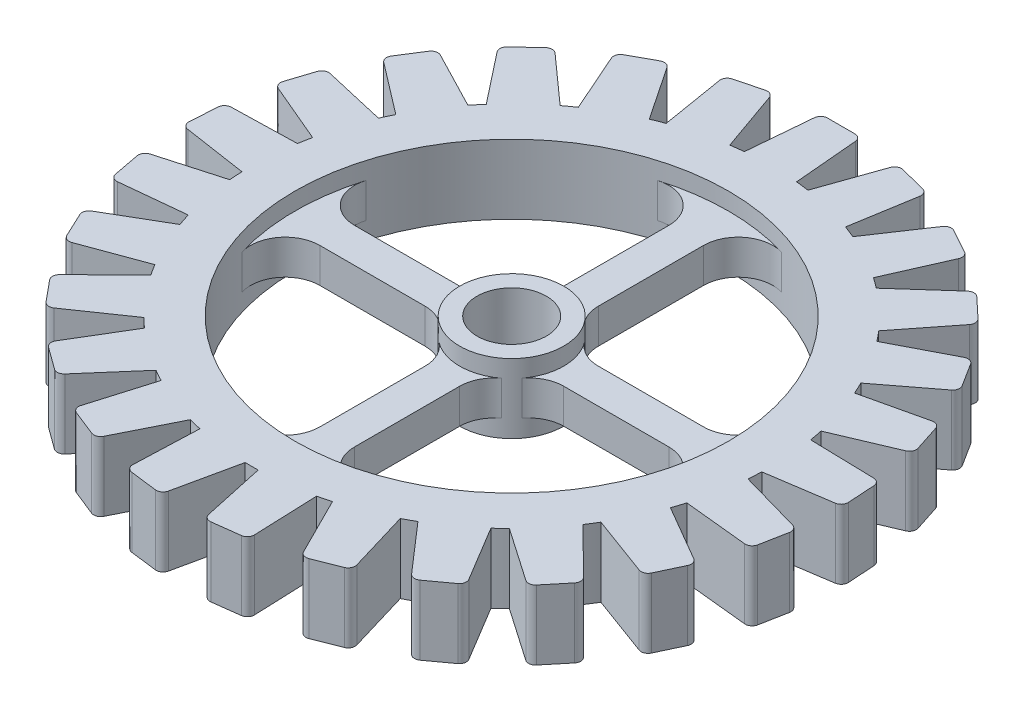
SolidWorks part; units mm, degrees
material "Gray Cast Iron"
ref_plane "Front Plane" through (0, 0, 0) normal (0, 0, 1) x (1, 0, 0)
ref_plane "Top Plane" through (0, 0, 0) normal (0, 1, 0) x (1, 0, 0)
ref_plane "Right Plane" through (0, 0, 0) normal (1, 0, 0) x (0, 0, -1)
sketch "Sketch1" plane through (0, 0, 0) normal (0, 1, 0) x (1, 0, 0)
  line L0 (0, -105.985) -> (0, 121.1882) construction
  line L1 (-7.5, 75) -> (7.5, 75) construction
  line L2 (-7.5, 75) -> (-5.91, 93.1743)
  line L3 (0, 95) -> (0, 75)
  line L4 (-3.9176, 95) -> (3.9176, 95)
  line L6 (-7.5332, 74.6207) -> (-7.5, 75)
  line L7 (7.5, 75) -> (5.91, 93.1743)
  line L8 (7.5332, 74.6207) -> (7.5, 75)
  line L9 (11.3874, 74.5089) -> (17.4472, 91.7168)
  line L10 (19.8311, 92.9897) -> (27.42, 91.0411)
  line L11 (25.9161, 70.7786) -> (28.8958, 88.7773)
  line L12 (25.8539, 70.4029) -> (25.9161, 70.7786)
  line L13 (11.2609, 74.1498) -> (11.3874, 74.5089)
  line L14 (29.5592, 69.3362) -> (39.7081, 84.4964)
  line L15 (42.3336, 85.1364) -> (49.1996, 81.3618)
  line L16 (42.7038, 62.1098) -> (50.066, 78.8021)
  line L17 (42.5502, 61.7615) -> (42.7038, 62.1098)
  line L18 (29.3474, 69.0198) -> (29.5592, 69.3362)
  line L19 (45.8738, 59.8068) -> (59.474, 71.9668)
  line L20 (62.1762, 71.9338) -> (67.8878, 66.5703)
  line L21 (56.8083, 49.5385) -> (68.0904, 63.8755)
  line L22 (56.5728, 49.2393) -> (56.8083, 49.5385)
  line L23 (45.5899, 59.553) -> (45.8738, 59.8068)
  line L24 (59.3059, 46.5195) -> (75.503, 54.9152)
  line L25 (78.112, 54.2113) -> (82.3103, 47.5958)
  line L26 (67.3433, 33.8546) -> (81.8364, 44.9354)
  line L27 (67.0408, 33.6233) -> (67.3433, 33.8546)
  line L28 (58.9679, 46.3443) -> (59.3059, 46.5195)
  line L29 (69.0116, 30.3092) -> (86.7878, 34.4131)
  line L30 (89.1398, 33.0824) -> (91.561, 25.6308)
  line L31 (73.6469, 16.0434) -> (90.4403, 23.1717)
  line L32 (73.2964, 15.8946) -> (73.6469, 16.0434)
  line L33 (68.6406, 30.2236) -> (69.0116, 30.3092)
  line L34 (74.3811, 12.1945) -> (92.6194, 11.7488)
  line L35 (94.5666, 9.8749) -> (95.0585, 2.0553)
  line L36 (75.3229, -2.7759) -> (93.3615, -0.0478)
  line L37 (74.9465, -2.8328) -> (75.3229, -2.7759)
  line L38 (74.0005, 12.2038) -> (74.3811, 12.1945)
  line L39 (75.0769, -6.6864) -> (92.6314, -11.6539)
  line L40 (94.0514, -13.9531) -> (92.5832, -21.6494)
  line L41 (72.2662, -21.4208) -> (90.4165, -23.2644)
  line L42 (71.8874, -21.3823) -> (72.2662, -21.4208)
  line L43 (74.7106, -6.5828) -> (75.0769, -6.6864)
  line L44 (71.0554, -25.1472) -> (86.823, -34.3242)
  line L45 (87.6266, -36.9043) -> (84.2906, -43.9938)
  line L46 (64.6687, -38.7196) -> (81.7903, -45.0192)
  line L47 (64.3114, -38.5882) -> (64.6687, -38.7196)
  line L48 (70.7263, -24.9557) -> (71.0554, -25.1472)
  line L49 (62.5692, -42.0279) -> (75.5592, -54.8378)
  line L50 (75.6959, -57.5367) -> (70.7016, -63.5738)
  line L51 (53.0078, -53.5856) -> (68.0249, -63.9452)
  line L52 (52.6944, -53.3695) -> (53.0078, -53.5856)
  line L53 (62.2981, -41.7606) -> (62.5692, -42.0279)
  line L54 (50.1515, -56.2679) -> (59.5477, -71.9058)
  line L55 (59.009, -74.5539) -> (52.6702, -79.1593)
  line L56 (38.0163, -65.0847) -> (49.9852, -78.8534)
  line L57 (37.7665, -64.7973) -> (38.0163, -65.0847)
  line L58 (49.9554, -55.9415) -> (50.1515, -56.2679)
  line L59 (34.5827, -66.9723) -> (39.7947, -84.4557)
  line L60 (38.6143, -86.8866) -> (31.3294, -89.7709)
  line L61 (20.636, -72.4942) -> (28.8048, -88.8069)
  line L62 (20.4655, -72.1537) -> (20.636, -72.4942)
  line L63 (34.4739, -66.6074) -> (34.5827, -66.9723)
  line L64 (16.8409, -73.4686) -> (17.5412, -91.6989)
  line L65 (15.7933, -93.7599) -> (8.02, -94.7419)
  line L66 (1.9591, -75.3486) -> (5.8145, -93.1803)
  line L67 (1.8787, -74.9765) -> (1.9591, -75.3486)
  line L68 (16.8262, -73.0882) -> (16.8409, -73.4686)
  line L69 (-1.9591, -75.3486) -> (-5.8145, -93.1803)
  line L70 (-8.02, -94.7419) -> (-15.7933, -93.7599)
  line L71 (-16.8409, -73.4686) -> (-17.5412, -91.6989)
  line L72 (-16.8262, -73.0882) -> (-16.8409, -73.4686)
  line L73 (-1.8787, -74.9765) -> (-1.9591, -75.3486)
  line L74 (-20.636, -72.4942) -> (-28.8048, -88.8069)
  line L75 (-31.3294, -89.7709) -> (-38.6143, -86.8866)
  line L76 (-34.5827, -66.9723) -> (-39.7947, -84.4557)
  line L77 (-34.4739, -66.6074) -> (-34.5827, -66.9723)
  line L78 (-20.4655, -72.1537) -> (-20.636, -72.4942)
  line L79 (-38.0163, -65.0847) -> (-49.9852, -78.8534)
  line L80 (-52.6702, -79.1593) -> (-59.009, -74.5539)
  line L81 (-50.1515, -56.2679) -> (-59.5477, -71.9058)
  line L82 (-49.9554, -55.9415) -> (-50.1515, -56.2679)
  line L83 (-37.7665, -64.7973) -> (-38.0163, -65.0847)
  line L84 (-53.0078, -53.5856) -> (-68.0249, -63.9452)
  line L85 (-70.7016, -63.5738) -> (-75.6959, -57.5367)
  line L86 (-62.5692, -42.0279) -> (-75.5592, -54.8378)
  line L87 (-62.2981, -41.7606) -> (-62.5692, -42.0279)
  line L88 (-52.6944, -53.3695) -> (-53.0078, -53.5856)
  line L89 (-64.6687, -38.7196) -> (-81.7903, -45.0192)
  line L90 (-84.2906, -43.9938) -> (-87.6266, -36.9043)
  line L91 (-71.0554, -25.1472) -> (-86.823, -34.3242)
  line L92 (-70.7263, -24.9557) -> (-71.0554, -25.1472)
  line L93 (-64.3114, -38.5882) -> (-64.6687, -38.7196)
  line L94 (-72.2662, -21.4208) -> (-90.4165, -23.2644)
  line L95 (-92.5832, -21.6494) -> (-94.0514, -13.9531)
  line L96 (-75.0769, -6.6864) -> (-92.6314, -11.6539)
  line L97 (-74.7106, -6.5828) -> (-75.0769, -6.6864)
  line L98 (-71.8874, -21.3823) -> (-72.2662, -21.4208)
  line L99 (-75.3229, -2.7759) -> (-93.3615, -0.0478)
  line L100 (-95.0585, 2.0553) -> (-94.5666, 9.8749)
  line L101 (-74.3811, 12.1945) -> (-92.6194, 11.7488)
  line L102 (-74.0005, 12.2038) -> (-74.3811, 12.1945)
  line L103 (-74.9465, -2.8328) -> (-75.3229, -2.7759)
  line L104 (-73.6469, 16.0434) -> (-90.4403, 23.1717)
  line L105 (-91.561, 25.6308) -> (-89.1398, 33.0824)
  line L106 (-69.0116, 30.3092) -> (-86.7878, 34.4131)
  line L107 (-68.6406, 30.2236) -> (-69.0116, 30.3092)
  line L108 (-73.2964, 15.8946) -> (-73.6469, 16.0434)
  line L109 (-67.3433, 33.8546) -> (-81.8364, 44.9354)
  line L110 (-82.3103, 47.5958) -> (-78.112, 54.2113)
  line L111 (-59.3059, 46.5195) -> (-75.503, 54.9152)
  line L112 (-58.9679, 46.3443) -> (-59.3059, 46.5195)
  line L113 (-67.0408, 33.6233) -> (-67.3433, 33.8546)
  line L114 (-56.8083, 49.5385) -> (-68.0904, 63.8755)
  line L115 (-67.8878, 66.5703) -> (-62.1762, 71.9338)
  line L116 (-45.8738, 59.8068) -> (-59.474, 71.9668)
  line L117 (-45.5899, 59.553) -> (-45.8738, 59.8068)
  line L118 (-56.5728, 49.2393) -> (-56.8083, 49.5385)
  line L119 (-42.7038, 62.1098) -> (-50.066, 78.8021)
  line L120 (-49.1996, 81.3618) -> (-42.3336, 85.1364)
  line L121 (-29.5592, 69.3362) -> (-39.7081, 84.4964)
  line L122 (-29.3474, 69.0198) -> (-29.5592, 69.3362)
  line L123 (-42.5502, 61.7615) -> (-42.7038, 62.1098)
  line L124 (-25.9161, 70.7786) -> (-28.8958, 88.7773)
  line L125 (-27.42, 91.0411) -> (-19.8311, 92.9897)
  line L126 (-11.3874, 74.5089) -> (-17.4472, 91.7168)
  line L127 (-11.2609, 74.1498) -> (-11.3874, 74.5089)
  line L128 (-25.8539, 70.4029) -> (-25.9161, 70.7786)
  arc A0 (-42.5502, 61.7615) -> (-45.5899, 59.553) centre (0, 0) ccw
  arc A1 (-5.91, 93.1743) -> (-3.9176, 95) centre (-3.9176, 93) cw
  arc A2 (5.91, 93.1743) -> (3.9176, 95) centre (3.9176, 93) ccw
  arc A3 (17.4472, 91.7168) -> (19.8311, 92.9897) centre (19.3337, 91.0525) cw
  arc A4 (28.8958, 88.7773) -> (27.42, 91.0411) centre (26.9226, 89.104) ccw
  arc A5 (39.7081, 84.4964) -> (42.3336, 85.1364) centre (41.3701, 83.3838) cw
  arc A6 (50.066, 78.8021) -> (49.1996, 81.3618) centre (48.2361, 79.6092) ccw
  arc A7 (59.474, 71.9668) -> (62.1762, 71.9338) centre (60.8071, 70.4758) cw
  arc A8 (68.0904, 63.8755) -> (67.8878, 66.5703) centre (66.5187, 65.1123) ccw
  arc A9 (75.503, 54.9152) -> (78.112, 54.2113) centre (76.4234, 53.1396) cw
  arc A10 (81.8364, 44.9354) -> (82.3103, 47.5958) centre (80.6216, 46.5242) ccw
  arc A11 (86.7878, 34.4131) -> (89.1398, 33.0824) centre (87.2377, 32.4644) cw
  arc A12 (90.4403, 23.1717) -> (91.561, 25.6308) centre (89.6588, 25.0128) ccw
  arc A13 (92.6194, 11.7488) -> (94.5666, 9.8749) centre (92.5705, 9.7494) cw
  arc A14 (93.3615, -0.0478) -> (95.0585, 2.0553) centre (93.0625, 1.9297) ccw
  arc A15 (92.6314, -11.6539) -> (94.0514, -13.9531) centre (92.0868, -13.5783) cw
  arc A16 (90.4165, -23.2644) -> (92.5832, -21.6494) centre (90.6186, -21.2746) ccw
  arc A17 (86.823, -34.3242) -> (87.6266, -36.9043) centre (85.8169, -36.0528) cw
  arc A18 (81.7903, -45.0192) -> (84.2906, -43.9938) centre (82.4809, -43.1422) ccw
  arc A19 (75.5592, -54.8378) -> (75.6959, -57.5367) centre (74.1549, -56.2619) cw
  arc A20 (68.0249, -63.9452) -> (70.7016, -63.5738) centre (69.1606, -62.299) ccw
  arc A21 (59.5477, -71.9058) -> (59.009, -74.5539) centre (57.8334, -72.9359) cw
  arc A22 (49.9852, -78.8534) -> (52.6702, -79.1593) centre (51.4947, -77.5413) ccw
  arc A23 (39.7947, -84.4557) -> (38.6143, -86.8866) centre (37.878, -85.0271) cw
  arc A24 (28.8048, -88.8069) -> (31.3294, -89.7709) centre (30.5931, -87.9114) ccw
  arc A25 (17.5412, -91.6989) -> (15.7933, -93.7599) centre (15.5427, -91.7757) cw
  arc A26 (5.8145, -93.1803) -> (8.02, -94.7419) centre (7.7693, -92.7577) ccw
  arc A27 (-5.8145, -93.1803) -> (-8.02, -94.7419) centre (-7.7693, -92.7577) cw
  arc A28 (-17.5412, -91.6989) -> (-15.7933, -93.7599) centre (-15.5427, -91.7757) ccw
  arc A29 (-28.8048, -88.8069) -> (-31.3294, -89.7709) centre (-30.5931, -87.9114) cw
  arc A30 (-39.7947, -84.4557) -> (-38.6143, -86.8866) centre (-37.878, -85.0271) ccw
  arc A31 (-49.9852, -78.8534) -> (-52.6702, -79.1593) centre (-51.4947, -77.5413) cw
  arc A32 (-59.5477, -71.9058) -> (-59.009, -74.5539) centre (-57.8334, -72.9359) ccw
  arc A33 (-68.0249, -63.9452) -> (-70.7016, -63.5738) centre (-69.1606, -62.299) cw
  arc A34 (-75.5592, -54.8378) -> (-75.6959, -57.5367) centre (-74.1549, -56.2619) ccw
  arc A35 (-81.7903, -45.0192) -> (-84.2906, -43.9938) centre (-82.4809, -43.1422) cw
  arc A36 (-86.823, -34.3242) -> (-87.6266, -36.9043) centre (-85.8169, -36.0528) ccw
  arc A37 (-90.4165, -23.2644) -> (-92.5832, -21.6494) centre (-90.6186, -21.2746) cw
  arc A38 (-92.6314, -11.6539) -> (-94.0514, -13.9531) centre (-92.0868, -13.5783) ccw
  arc A39 (-93.3615, -0.0478) -> (-95.0585, 2.0553) centre (-93.0625, 1.9297) cw
  arc A40 (-92.6194, 11.7488) -> (-94.5666, 9.8749) centre (-92.5705, 9.7494) ccw
  arc A41 (-90.4403, 23.1717) -> (-91.561, 25.6308) centre (-89.6588, 25.0128) cw
  arc A42 (-86.7878, 34.4131) -> (-89.1398, 33.0824) centre (-87.2377, 32.4644) ccw
  arc A43 (-81.8364, 44.9354) -> (-82.3103, 47.5958) centre (-80.6216, 46.5242) cw
  arc A44 (-75.503, 54.9152) -> (-78.112, 54.2113) centre (-76.4234, 53.1396) ccw
  arc A45 (-68.0904, 63.8755) -> (-67.8878, 66.5703) centre (-66.5187, 65.1123) cw
  arc A46 (-59.474, 71.9668) -> (-62.1762, 71.9338) centre (-60.8071, 70.4758) ccw
  arc A47 (-50.066, 78.8021) -> (-49.1996, 81.3618) centre (-48.2361, 79.6092) cw
  arc A48 (-39.7081, 84.4964) -> (-42.3336, 85.1364) centre (-41.3701, 83.3838) ccw
  arc A49 (-28.8958, 88.7773) -> (-27.42, 91.0411) centre (-26.9226, 89.104) cw
  arc A50 (-17.4472, 91.7168) -> (-19.8311, 92.9897) centre (-19.3337, 91.0525) ccw
  arc A51 (-25.8539, 70.4029) -> (-29.3474, 69.0198) centre (0, 0) ccw
  arc A52 (-7.5332, 74.6207) -> (-11.2609, 74.1498) centre (0, 0) ccw
  arc A53 (11.2609, 74.1498) -> (7.5332, 74.6207) centre (0, 0) ccw
  arc A54 (29.3474, 69.0198) -> (25.8539, 70.4029) centre (0, 0) ccw
  arc A55 (45.5899, 59.553) -> (42.5502, 61.7615) centre (0, 0) ccw
  arc A56 (58.9679, 46.3443) -> (56.5728, 49.2393) centre (0, 0) ccw
  arc A57 (74.0005, 12.2038) -> (73.2964, 15.8946) centre (0, 0) ccw
  arc A58 (68.6406, 30.2236) -> (67.0408, 33.6233) centre (0, 0) ccw
  arc A59 (74.7106, -6.5828) -> (74.9465, -2.8328) centre (0, 0) ccw
  arc A60 (70.7263, -24.9557) -> (71.8874, -21.3823) centre (0, 0) ccw
  arc A61 (62.2981, -41.7606) -> (64.3114, -38.5882) centre (0, 0) ccw
  arc A62 (49.9554, -55.9415) -> (52.6944, -53.3695) centre (0, 0) ccw
  arc A63 (34.4739, -66.6074) -> (37.7665, -64.7973) centre (0, 0) ccw
  arc A64 (16.8262, -73.0882) -> (20.4655, -72.1537) centre (0, 0) ccw
  arc A65 (-1.8787, -74.9765) -> (1.8787, -74.9765) centre (0, 0) ccw
  arc A66 (-20.4655, -72.1537) -> (-16.8262, -73.0882) centre (0, 0) ccw
  arc A67 (-37.7665, -64.7973) -> (-34.4739, -66.6074) centre (0, 0) ccw
  arc A68 (-52.6944, -53.3695) -> (-49.9554, -55.9415) centre (0, 0) ccw
  arc A69 (-64.3114, -38.5882) -> (-62.2981, -41.7606) centre (0, 0) ccw
  arc A70 (-71.8874, -21.3823) -> (-70.7263, -24.9557) centre (0, 0) ccw
  arc A71 (-74.9465, -2.8328) -> (-74.7106, -6.5828) centre (0, 0) ccw
  arc A72 (-73.2964, 15.8946) -> (-74.0005, 12.2038) centre (0, 0) ccw
  arc A73 (-67.0408, 33.6233) -> (-68.6406, 30.2236) centre (0, 0) ccw
  arc A74 (-56.5728, 49.2393) -> (-58.9679, 46.3443) centre (0, 0) ccw
  point P1 (-63.4444, 95.72)
  point P260 (0, 0)
  dimension "D1" = 150
  dimension "D5" = 2
  dimension "D2" = 15
  dimension "D4" = 85
  dimension "D7" = 20
  dimension "D6" = 25
extrude "Boss-Extrude1" add sketch "Sketch1" along normal blind 20 contours L118 A74 L112 L111 A44 L110 A43 L109 L113 A73 L107 L106 A42 L105 A41 L104 L108 A72 L102 L101 A40 L100 A39 L99 L103 A71 L97 L96 A38 L95 A37 L94 L98 A70 L92 L91 A36 L90 A35 L89 L93 A69 L87 L86 A34 L85 A33 L84 L88 A68 L82
sketch "Sketch2" plane through (0, 0, 0) normal (0, -1, 0) x (1, 0, 0)
  line L75 (-56.5728, -49.2393) -> (-68.0904, -63.8755)
  line L76 (-67.8878, -66.5703) -> (-62.1762, -71.9338)
  line L77 (-59.474, -71.9668) -> (-45.5899, -59.553)
  line L78 (-42.5502, -61.7615) -> (-50.066, -78.8021)
  line L79 (-49.1996, -81.3618) -> (-42.3336, -85.1364)
  line L80 (-39.7081, -84.4964) -> (-29.3474, -69.0198)
  line L81 (-25.8539, -70.4029) -> (-28.8958, -88.7773)
  line L82 (-27.42, -91.0411) -> (-19.8311, -92.9897)
  line L83 (-17.4472, -91.7168) -> (-11.2609, -74.1498)
  line L84 (-7.5332, -74.6207) -> (-5.91, -93.1743)
  line L85 (-3.9176, -95) -> (3.9176, -95)
  line L86 (5.91, -93.1743) -> (7.5332, -74.6207)
  line L87 (11.2609, -74.1498) -> (17.4472, -91.7168)
  line L88 (19.8311, -92.9897) -> (27.42, -91.0411)
  line L89 (28.8958, -88.7773) -> (25.8539, -70.4029)
  line L90 (29.3474, -69.0198) -> (39.7081, -84.4964)
  line L91 (42.3336, -85.1364) -> (49.1996, -81.3618)
  line L92 (50.066, -78.8021) -> (42.5502, -61.7615)
  line L93 (45.5899, -59.553) -> (59.474, -71.9668)
  line L94 (62.1762, -71.9338) -> (67.8878, -66.5703)
  line L95 (68.0904, -63.8755) -> (56.5728, -49.2393)
  line L96 (58.9679, -46.3443) -> (75.503, -54.9152)
  line L97 (78.112, -54.2113) -> (82.3103, -47.5958)
  line L98 (81.8364, -44.9354) -> (67.0408, -33.6233)
  line L99 (68.6406, -30.2236) -> (86.7878, -34.4131)
  line L100 (89.1398, -33.0824) -> (91.561, -25.6308)
  line L101 (90.4403, -23.1717) -> (73.2964, -15.8946)
  line L102 (74.0005, -12.2038) -> (92.6194, -11.7488)
  line L103 (94.5666, -9.8749) -> (95.0585, -2.0553)
  line L104 (93.3615, 0.0478) -> (74.9465, 2.8328)
  line L105 (74.7106, 6.5828) -> (92.6314, 11.6539)
  line L106 (94.0514, 13.9531) -> (92.5832, 21.6494)
  line L107 (90.4165, 23.2644) -> (71.8874, 21.3823)
  line L108 (70.7263, 24.9557) -> (86.823, 34.3242)
  line L109 (87.6266, 36.9043) -> (84.2906, 43.9938)
  line L110 (81.7903, 45.0192) -> (64.3114, 38.5882)
  line L111 (62.2981, 41.7606) -> (75.5592, 54.8378)
  line L112 (75.6959, 57.5367) -> (70.7016, 63.5738)
  line L113 (68.0249, 63.9452) -> (52.6944, 53.3695)
  line L114 (49.9554, 55.9415) -> (59.5477, 71.9058)
  line L115 (59.009, 74.5539) -> (52.6702, 79.1593)
  line L116 (49.9852, 78.8534) -> (37.7665, 64.7973)
  line L117 (34.4739, 66.6074) -> (39.7947, 84.4557)
  line L118 (38.6143, 86.8866) -> (31.3294, 89.7709)
  line L119 (28.8048, 88.8069) -> (20.4655, 72.1537)
  line L120 (16.8262, 73.0882) -> (17.5412, 91.6989)
  line L121 (15.7933, 93.7599) -> (8.02, 94.7419)
  line L122 (5.8145, 93.1803) -> (1.8787, 74.9765)
  line L123 (-1.8787, 74.9765) -> (-5.8145, 93.1803)
  line L124 (-8.02, 94.7419) -> (-15.7933, 93.7599)
  line L125 (-17.5412, 91.6989) -> (-16.8262, 73.0882)
  line L126 (-20.4655, 72.1537) -> (-28.8048, 88.8069)
  line L127 (-31.3294, 89.7709) -> (-38.6143, 86.8866)
  line L128 (-39.7947, 84.4557) -> (-34.4739, 66.6074)
  line L129 (-37.7665, 64.7973) -> (-49.9852, 78.8534)
  line L130 (-52.6702, 79.1593) -> (-59.009, 74.5539)
  line L131 (-59.5477, 71.9058) -> (-49.9554, 55.9415)
  line L132 (-52.6944, 53.3695) -> (-68.0249, 63.9452)
  line L133 (-70.7016, 63.5738) -> (-75.6959, 57.5367)
  line L134 (-75.5592, 54.8378) -> (-62.2981, 41.7606)
  line L135 (-64.3114, 38.5882) -> (-81.7903, 45.0192)
  line L136 (-84.2906, 43.9938) -> (-87.6266, 36.9043)
  line L137 (-86.823, 34.3242) -> (-70.7263, 24.9557)
  line L138 (-71.8874, 21.3823) -> (-90.4165, 23.2644)
  line L139 (-92.5832, 21.6494) -> (-94.0514, 13.9531)
  line L140 (-92.6314, 11.6539) -> (-74.7106, 6.5828)
  line L141 (-74.9465, 2.8328) -> (-93.3615, 0.0478)
  line L142 (-95.0585, -2.0553) -> (-94.5666, -9.8749)
  line L143 (-92.6194, -11.7488) -> (-74.0005, -12.2038)
  line L144 (-73.2964, -15.8946) -> (-90.4403, -23.1717)
  line L145 (-91.561, -25.6308) -> (-89.1398, -33.0824)
  line L146 (-86.7878, -34.4131) -> (-68.6406, -30.2236)
  line L147 (-67.0408, -33.6233) -> (-81.8364, -44.9354)
  line L148 (-82.3103, -47.5958) -> (-78.112, -54.2113)
  line L149 (-75.503, -54.9152) -> (-58.9679, -46.3443)
  line L150 (-56.5728, -49.2393) -> (-68.0904, -63.8755)
  line L151 (-67.8878, -66.5703) -> (-62.1762, -71.9338)
  line L152 (-59.474, -71.9668) -> (-45.5899, -59.553)
  line L153 (-42.5502, -61.7615) -> (-50.066, -78.8021)
  line L154 (-49.1996, -81.3618) -> (-42.3336, -85.1364)
  line L155 (-39.7081, -84.4964) -> (-29.3474, -69.0198)
  line L156 (-25.8539, -70.4029) -> (-28.8958, -88.7773)
  line L157 (-27.42, -91.0411) -> (-19.8311, -92.9897)
  line L158 (-17.4472, -91.7168) -> (-11.2609, -74.1498)
  line L159 (-7.5332, -74.6207) -> (-5.91, -93.1743)
  line L160 (-3.9176, -95) -> (3.9176, -95)
  line L161 (5.91, -93.1743) -> (7.5332, -74.6207)
  line L162 (11.2609, -74.1498) -> (17.4472, -91.7168)
  line L163 (19.8311, -92.9897) -> (27.42, -91.0411)
  line L164 (28.8958, -88.7773) -> (25.8539, -70.4029)
  line L165 (29.3474, -69.0198) -> (39.7081, -84.4964)
  line L166 (42.3336, -85.1364) -> (49.1996, -81.3618)
  line L167 (50.066, -78.8021) -> (42.5502, -61.7615)
  line L168 (45.5899, -59.553) -> (59.474, -71.9668)
  line L169 (62.1762, -71.9338) -> (67.8878, -66.5703)
  line L170 (68.0904, -63.8755) -> (56.5728, -49.2393)
  line L171 (58.9679, -46.3443) -> (75.503, -54.9152)
  line L172 (78.112, -54.2113) -> (82.3103, -47.5958)
  line L173 (81.8364, -44.9354) -> (67.0408, -33.6233)
  line L174 (68.6406, -30.2236) -> (86.7878, -34.4131)
  line L175 (89.1398, -33.0824) -> (91.561, -25.6308)
  line L176 (90.4403, -23.1717) -> (73.2964, -15.8946)
  line L177 (74.0005, -12.2038) -> (92.6194, -11.7488)
  line L178 (94.5666, -9.8749) -> (95.0585, -2.0553)
  line L179 (93.3615, 0.0478) -> (74.9465, 2.8328)
  line L180 (74.7106, 6.5828) -> (92.6314, 11.6539)
  line L181 (94.0514, 13.9531) -> (92.5832, 21.6494)
  line L182 (90.4165, 23.2644) -> (71.8874, 21.3823)
  line L183 (70.7263, 24.9557) -> (86.823, 34.3242)
  line L184 (87.6266, 36.9043) -> (84.2906, 43.9938)
  line L185 (81.7903, 45.0192) -> (64.3114, 38.5882)
  line L186 (62.2981, 41.7606) -> (75.5592, 54.8378)
  line L187 (75.6959, 57.5367) -> (70.7016, 63.5738)
  line L188 (68.0249, 63.9452) -> (52.6944, 53.3695)
  line L189 (49.9554, 55.9415) -> (59.5477, 71.9058)
  line L190 (59.009, 74.5539) -> (52.6702, 79.1593)
  line L191 (49.9852, 78.8534) -> (37.7665, 64.7973)
  line L192 (34.4739, 66.6074) -> (39.7947, 84.4557)
  line L193 (38.6143, 86.8866) -> (31.3294, 89.7709)
  line L194 (28.8048, 88.8069) -> (20.4655, 72.1537)
  line L195 (16.8262, 73.0882) -> (17.5412, 91.6989)
  line L196 (15.7933, 93.7599) -> (8.02, 94.7419)
  line L197 (5.8145, 93.1803) -> (1.8787, 74.9765)
  line L198 (-1.8787, 74.9765) -> (-5.8145, 93.1803)
  line L199 (-8.02, 94.7419) -> (-15.7933, 93.7599)
  line L200 (-17.5412, 91.6989) -> (-16.8262, 73.0882)
  line L201 (-20.4655, 72.1537) -> (-28.8048, 88.8069)
  line L202 (-31.3294, 89.7709) -> (-38.6143, 86.8866)
  line L203 (-39.7947, 84.4557) -> (-34.4739, 66.6074)
  line L204 (-37.7665, 64.7973) -> (-49.9852, 78.8534)
  line L205 (-52.6702, 79.1593) -> (-59.009, 74.5539)
  line L206 (-59.5477, 71.9058) -> (-49.9554, 55.9415)
  line L207 (-52.6944, 53.3695) -> (-68.0249, 63.9452)
  line L208 (-70.7016, 63.5738) -> (-75.6959, 57.5367)
  line L209 (-75.5592, 54.8378) -> (-62.2981, 41.7606)
  line L210 (-64.3114, 38.5882) -> (-81.7903, 45.0192)
  line L211 (-84.2906, 43.9938) -> (-87.6266, 36.9043)
  line L212 (-86.823, 34.3242) -> (-70.7263, 24.9557)
  line L213 (-71.8874, 21.3823) -> (-90.4165, 23.2644)
  line L214 (-92.5832, 21.6494) -> (-94.0514, 13.9531)
  line L215 (-92.6314, 11.6539) -> (-74.7106, 6.5828)
  line L216 (-74.9465, 2.8328) -> (-93.3615, 0.0478)
  line L217 (-95.0585, -2.0553) -> (-94.5666, -9.8749)
  line L218 (-92.6194, -11.7488) -> (-74.0005, -12.2038)
  line L219 (-73.2964, -15.8946) -> (-90.4403, -23.1717)
  line L220 (-91.561, -25.6308) -> (-89.1398, -33.0824)
  line L221 (-86.7878, -34.4131) -> (-68.6406, -30.2236)
  line L222 (-67.0408, -33.6233) -> (-81.8364, -44.9354)
  line L223 (-82.3103, -47.5958) -> (-78.112, -54.2113)
  line L224 (-75.503, -54.9152) -> (-58.9679, -46.3443)
  circle A0 centre (0, 0) radius 10
  arc A75 (-68.0904, -63.8755) -> (-67.8878, -66.5703) centre (-66.5187, -65.1123) ccw
  arc A76 (-62.1762, -71.9338) -> (-59.474, -71.9668) centre (-60.8071, -70.4758) ccw
  arc A77 (-45.5899, -59.553) -> (-42.5502, -61.7615) centre (0, 0) ccw
  arc A78 (-50.066, -78.8021) -> (-49.1996, -81.3618) centre (-48.2361, -79.6092) ccw
  arc A79 (-42.3336, -85.1364) -> (-39.7081, -84.4964) centre (-41.3701, -83.3838) ccw
  arc A80 (-29.3474, -69.0198) -> (-25.8539, -70.4029) centre (0, 0) ccw
  arc A82 (-19.8311, -92.9897) -> (-17.4472, -91.7168) centre (-19.3337, -91.0525) ccw
  arc A83 (-11.2609, -74.1498) -> (-7.5332, -74.6207) centre (0, 0) ccw
  arc A84 (-5.91, -93.1743) -> (-3.9176, -95) centre (-3.9176, -93) ccw
  arc A85 (3.9176, -95) -> (5.91, -93.1743) centre (3.9176, -93) ccw
  arc A86 (7.5332, -74.6207) -> (11.2609, -74.1498) centre (0, 0) ccw
  arc A87 (17.4472, -91.7168) -> (19.8311, -92.9897) centre (19.3337, -91.0525) ccw
  arc A88 (27.42, -91.0411) -> (28.8958, -88.7773) centre (26.9226, -89.104) ccw
  arc A89 (25.8539, -70.4029) -> (29.3474, -69.0198) centre (0, 0) ccw
  arc A90 (39.7081, -84.4964) -> (42.3336, -85.1364) centre (41.3701, -83.3838) ccw
  arc A91 (49.1996, -81.3618) -> (50.066, -78.8021) centre (48.2361, -79.6092) ccw
  arc A92 (42.5502, -61.7615) -> (45.5899, -59.553) centre (0, 0) ccw
  arc A93 (59.474, -71.9668) -> (62.1762, -71.9338) centre (60.8071, -70.4758) ccw
  arc A94 (67.8878, -66.5703) -> (68.0904, -63.8755) centre (66.5187, -65.1123) ccw
  arc A95 (56.5728, -49.2393) -> (58.9679, -46.3443) centre (0, 0) ccw
  arc A96 (75.503, -54.9152) -> (78.112, -54.2113) centre (76.4234, -53.1396) ccw
  arc A97 (82.3103, -47.5958) -> (81.8364, -44.9354) centre (80.6216, -46.5242) ccw
  arc A98 (67.0408, -33.6233) -> (68.6406, -30.2236) centre (0, 0) ccw
  arc A99 (86.7878, -34.4131) -> (89.1398, -33.0824) centre (87.2377, -32.4644) ccw
  arc A100 (91.561, -25.6308) -> (90.4403, -23.1717) centre (89.6588, -25.0128) ccw
  arc A101 (73.2964, -15.8946) -> (74.0005, -12.2038) centre (0, 0) ccw
  arc A102 (92.6194, -11.7488) -> (94.5666, -9.8749) centre (92.5705, -9.7494) ccw
  arc A103 (95.0585, -2.0553) -> (93.3615, 0.0478) centre (93.0625, -1.9297) ccw
  arc A104 (74.9465, 2.8328) -> (74.7106, 6.5828) centre (0, 0) ccw
  arc A105 (92.6314, 11.6539) -> (94.0514, 13.9531) centre (92.0868, 13.5783) ccw
  arc A106 (92.5832, 21.6494) -> (90.4165, 23.2644) centre (90.6186, 21.2746) ccw
  arc A107 (71.8874, 21.3823) -> (70.7263, 24.9557) centre (0, 0) ccw
  arc A108 (86.823, 34.3242) -> (87.6266, 36.9043) centre (85.8169, 36.0528) ccw
  arc A109 (84.2906, 43.9938) -> (81.7903, 45.0192) centre (82.4809, 43.1422) ccw
  arc A110 (64.3114, 38.5882) -> (62.2981, 41.7606) centre (0, 0) ccw
  arc A111 (75.5592, 54.8378) -> (75.6959, 57.5367) centre (74.1549, 56.2619) ccw
  arc A112 (70.7016, 63.5738) -> (68.0249, 63.9452) centre (69.1606, 62.299) ccw
  arc A113 (52.6944, 53.3695) -> (49.9554, 55.9415) centre (0, 0) ccw
  arc A114 (59.5477, 71.9058) -> (59.009, 74.5539) centre (57.8334, 72.9359) ccw
  arc A115 (52.6702, 79.1593) -> (49.9852, 78.8534) centre (51.4947, 77.5413) ccw
  arc A116 (37.7665, 64.7973) -> (34.4739, 66.6074) centre (0, 0) ccw
  arc A117 (39.7947, 84.4557) -> (38.6143, 86.8866) centre (37.878, 85.0271) ccw
  arc A118 (31.3294, 89.7709) -> (28.8048, 88.8069) centre (30.5931, 87.9114) ccw
  arc A119 (20.4655, 72.1537) -> (16.8262, 73.0882) centre (0, 0) ccw
  arc A120 (17.5412, 91.6989) -> (15.7933, 93.7599) centre (15.5427, 91.7757) ccw
  arc A121 (8.02, 94.7419) -> (5.8145, 93.1803) centre (7.7693, 92.7577) ccw
  arc A122 (1.8787, 74.9765) -> (-1.8787, 74.9765) centre (0, 0) ccw
  arc A123 (-5.8145, 93.1803) -> (-8.02, 94.7419) centre (-7.7693, 92.7577) ccw
  arc A124 (-15.7933, 93.7599) -> (-17.5412, 91.6989) centre (-15.5427, 91.7757) ccw
  arc A125 (-16.8262, 73.0882) -> (-20.4655, 72.1537) centre (0, 0) ccw
  arc A126 (-28.8048, 88.8069) -> (-31.3294, 89.7709) centre (-30.5931, 87.9114) ccw
  arc A127 (-38.6143, 86.8866) -> (-39.7947, 84.4557) centre (-37.878, 85.0271) ccw
  arc A128 (-34.4739, 66.6074) -> (-37.7665, 64.7973) centre (0, 0) ccw
  arc A129 (-49.9852, 78.8534) -> (-52.6702, 79.1593) centre (-51.4947, 77.5413) ccw
  arc A130 (-59.009, 74.5539) -> (-59.5477, 71.9058) centre (-57.8334, 72.9359) ccw
  arc A131 (-49.9554, 55.9415) -> (-52.6944, 53.3695) centre (0, 0) ccw
  arc A132 (-68.0249, 63.9452) -> (-70.7016, 63.5738) centre (-69.1606, 62.299) ccw
  arc A133 (-75.6959, 57.5367) -> (-75.5592, 54.8378) centre (-74.1549, 56.2619) ccw
  arc A134 (-62.2981, 41.7606) -> (-64.3114, 38.5882) centre (0, 0) ccw
  arc A135 (-81.7903, 45.0192) -> (-84.2906, 43.9938) centre (-82.4809, 43.1422) ccw
  arc A136 (-87.6266, 36.9043) -> (-86.823, 34.3242) centre (-85.8169, 36.0528) ccw
  arc A137 (-70.7263, 24.9557) -> (-71.8874, 21.3823) centre (0, 0) ccw
  arc A138 (-90.4165, 23.2644) -> (-92.5832, 21.6494) centre (-90.6186, 21.2746) ccw
  arc A139 (-94.0514, 13.9531) -> (-92.6314, 11.6539) centre (-92.0868, 13.5783) ccw
  arc A140 (-74.7106, 6.5828) -> (-74.9465, 2.8328) centre (0, 0) ccw
  arc A141 (-93.3615, 0.0478) -> (-95.0585, -2.0553) centre (-93.0625, -1.9297) ccw
  arc A142 (-94.5666, -9.8749) -> (-92.6194, -11.7488) centre (-92.5705, -9.7494) ccw
  arc A143 (-74.0005, -12.2038) -> (-73.2964, -15.8946) centre (0, 0) ccw
  arc A144 (-90.4403, -23.1717) -> (-91.561, -25.6308) centre (-89.6588, -25.0128) ccw
  arc A145 (-89.1398, -33.0824) -> (-86.7878, -34.4131) centre (-87.2377, -32.4644) ccw
  arc A146 (-68.6406, -30.2236) -> (-67.0408, -33.6233) centre (0, 0) ccw
  arc A147 (-81.8364, -44.9354) -> (-82.3103, -47.5958) centre (-80.6216, -46.5242) ccw
  arc A148 (-78.112, -54.2113) -> (-75.503, -54.9152) centre (-76.4234, -53.1396) ccw
  arc A149 (-58.9679, -46.3443) -> (-56.5728, -49.2393) centre (0, 0) ccw
  arc A150 (-68.0904, -63.8755) -> (-67.8878, -66.5703) centre (-66.5187, -65.1123) ccw
  arc A151 (-62.1762, -71.9338) -> (-59.474, -71.9668) centre (-60.8071, -70.4758) ccw
  arc A152 (-45.5899, -59.553) -> (-42.5502, -61.7615) centre (0, 0) ccw
  arc A153 (-50.066, -78.8021) -> (-49.1996, -81.3618) centre (-48.2361, -79.6092) ccw
  arc A154 (-42.3336, -85.1364) -> (-39.7081, -84.4964) centre (-41.3701, -83.3838) ccw
  arc A155 (-29.3474, -69.0198) -> (-25.8539, -70.4029) centre (0, 0) ccw
  arc A157 (-19.8311, -92.9897) -> (-17.4472, -91.7168) centre (-19.3337, -91.0525) ccw
  arc A158 (-11.2609, -74.1498) -> (-7.5332, -74.6207) centre (0, 0) ccw
  arc A159 (-5.91, -93.1743) -> (-3.9176, -95) centre (-3.9176, -93) ccw
  arc A160 (3.9176, -95) -> (5.91, -93.1743) centre (3.9176, -93) ccw
  arc A161 (7.5332, -74.6207) -> (11.2609, -74.1498) centre (0, 0) ccw
  arc A162 (17.4472, -91.7168) -> (19.8311, -92.9897) centre (19.3337, -91.0525) ccw
  arc A163 (27.42, -91.0411) -> (28.8958, -88.7773) centre (26.9226, -89.104) ccw
  arc A164 (25.8539, -70.4029) -> (29.3474, -69.0198) centre (0, 0) ccw
  arc A165 (39.7081, -84.4964) -> (42.3336, -85.1364) centre (41.3701, -83.3838) ccw
  arc A166 (49.1996, -81.3618) -> (50.066, -78.8021) centre (48.2361, -79.6092) ccw
  arc A167 (42.5502, -61.7615) -> (45.5899, -59.553) centre (0, 0) ccw
  arc A168 (59.474, -71.9668) -> (62.1762, -71.9338) centre (60.8071, -70.4758) ccw
  arc A169 (67.8878, -66.5703) -> (68.0904, -63.8755) centre (66.5187, -65.1123) ccw
  arc A170 (56.5728, -49.2393) -> (58.9679, -46.3443) centre (0, 0) ccw
  arc A171 (75.503, -54.9152) -> (78.112, -54.2113) centre (76.4234, -53.1396) ccw
  arc A172 (82.3103, -47.5958) -> (81.8364, -44.9354) centre (80.6216, -46.5242) ccw
  arc A173 (67.0408, -33.6233) -> (68.6406, -30.2236) centre (0, 0) ccw
  arc A174 (86.7878, -34.4131) -> (89.1398, -33.0824) centre (87.2377, -32.4644) ccw
  arc A175 (91.561, -25.6308) -> (90.4403, -23.1717) centre (89.6588, -25.0128) ccw
  arc A176 (73.2964, -15.8946) -> (74.0005, -12.2038) centre (0, 0) ccw
  arc A177 (92.6194, -11.7488) -> (94.5666, -9.8749) centre (92.5705, -9.7494) ccw
  arc A178 (95.0585, -2.0553) -> (93.3615, 0.0478) centre (93.0625, -1.9297) ccw
  arc A179 (74.9465, 2.8328) -> (74.7106, 6.5828) centre (0, 0) ccw
  arc A180 (92.6314, 11.6539) -> (94.0514, 13.9531) centre (92.0868, 13.5783) ccw
  arc A181 (92.5832, 21.6494) -> (90.4165, 23.2644) centre (90.6186, 21.2746) ccw
  arc A182 (71.8874, 21.3823) -> (70.7263, 24.9557) centre (0, 0) ccw
  arc A183 (86.823, 34.3242) -> (87.6266, 36.9043) centre (85.8169, 36.0528) ccw
  arc A184 (84.2906, 43.9938) -> (81.7903, 45.0192) centre (82.4809, 43.1422) ccw
  arc A185 (64.3114, 38.5882) -> (62.2981, 41.7606) centre (0, 0) ccw
  arc A186 (75.5592, 54.8378) -> (75.6959, 57.5367) centre (74.1549, 56.2619) ccw
  arc A187 (70.7016, 63.5738) -> (68.0249, 63.9452) centre (69.1606, 62.299) ccw
  arc A188 (52.6944, 53.3695) -> (49.9554, 55.9415) centre (0, 0) ccw
  arc A189 (59.5477, 71.9058) -> (59.009, 74.5539) centre (57.8334, 72.9359) ccw
  arc A190 (52.6702, 79.1593) -> (49.9852, 78.8534) centre (51.4947, 77.5413) ccw
  arc A191 (37.7665, 64.7973) -> (34.4739, 66.6074) centre (0, 0) ccw
  arc A192 (39.7947, 84.4557) -> (38.6143, 86.8866) centre (37.878, 85.0271) ccw
  arc A193 (31.3294, 89.7709) -> (28.8048, 88.8069) centre (30.5931, 87.9114) ccw
  arc A194 (20.4655, 72.1537) -> (16.8262, 73.0882) centre (0, 0) ccw
  arc A195 (17.5412, 91.6989) -> (15.7933, 93.7599) centre (15.5427, 91.7757) ccw
  arc A196 (8.02, 94.7419) -> (5.8145, 93.1803) centre (7.7693, 92.7577) ccw
  arc A197 (1.8787, 74.9765) -> (-1.8787, 74.9765) centre (0, 0) ccw
  arc A198 (-5.8145, 93.1803) -> (-8.02, 94.7419) centre (-7.7693, 92.7577) ccw
  arc A199 (-15.7933, 93.7599) -> (-17.5412, 91.6989) centre (-15.5427, 91.7757) ccw
  arc A200 (-16.8262, 73.0882) -> (-20.4655, 72.1537) centre (0, 0) ccw
  arc A201 (-28.8048, 88.8069) -> (-31.3294, 89.7709) centre (-30.5931, 87.9114) ccw
  arc A202 (-38.6143, 86.8866) -> (-39.7947, 84.4557) centre (-37.878, 85.0271) ccw
  arc A203 (-34.4739, 66.6074) -> (-37.7665, 64.7973) centre (0, 0) ccw
  arc A204 (-49.9852, 78.8534) -> (-52.6702, 79.1593) centre (-51.4947, 77.5413) ccw
  arc A205 (-59.009, 74.5539) -> (-59.5477, 71.9058) centre (-57.8334, 72.9359) ccw
  arc A206 (-49.9554, 55.9415) -> (-52.6944, 53.3695) centre (0, 0) ccw
  arc A207 (-68.0249, 63.9452) -> (-70.7016, 63.5738) centre (-69.1606, 62.299) ccw
  arc A208 (-75.6959, 57.5367) -> (-75.5592, 54.8378) centre (-74.1549, 56.2619) ccw
  arc A209 (-62.2981, 41.7606) -> (-64.3114, 38.5882) centre (0, 0) ccw
  arc A210 (-81.7903, 45.0192) -> (-84.2906, 43.9938) centre (-82.4809, 43.1422) ccw
  arc A211 (-87.6266, 36.9043) -> (-86.823, 34.3242) centre (-85.8169, 36.0528) ccw
  arc A212 (-70.7263, 24.9557) -> (-71.8874, 21.3823) centre (0, 0) ccw
  arc A213 (-90.4165, 23.2644) -> (-92.5832, 21.6494) centre (-90.6186, 21.2746) ccw
  arc A214 (-94.0514, 13.9531) -> (-92.6314, 11.6539) centre (-92.0868, 13.5783) ccw
  arc A215 (-74.7106, 6.5828) -> (-74.9465, 2.8328) centre (0, 0) ccw
  arc A216 (-93.3615, 0.0478) -> (-95.0585, -2.0553) centre (-93.0625, -1.9297) ccw
  arc A217 (-94.5666, -9.8749) -> (-92.6194, -11.7488) centre (-92.5705, -9.7494) ccw
  arc A218 (-74.0005, -12.2038) -> (-73.2964, -15.8946) centre (0, 0) ccw
  arc A219 (-90.4403, -23.1717) -> (-91.561, -25.6308) centre (-89.6588, -25.0128) ccw
  arc A220 (-89.1398, -33.0824) -> (-86.7878, -34.4131) centre (-87.2377, -32.4644) ccw
  arc A221 (-68.6406, -30.2236) -> (-67.0408, -33.6233) centre (0, 0) ccw
  arc A222 (-81.8364, -44.9354) -> (-82.3103, -47.5958) centre (-80.6216, -46.5242) ccw
  arc A223 (-78.112, -54.2113) -> (-75.503, -54.9152) centre (-76.4234, -53.1396) ccw
  arc A224 (-58.9679, -46.3443) -> (-56.5728, -49.2393) centre (0, 0) ccw
  arc A225 (-28.8958, -88.7773) -> (-27.42, -91.0411) centre (-26.9226, -89.104) ccw
  arc A226 (-28.8958, -88.7773) -> (-27.42, -91.0411) centre (-26.9226, -89.104) ccw
  dimension "D2" = 20
  dimension "D1" = 0
extrude "Cut-Extrude1" cut sketch "Sketch2" against normal through all contours A0
sketch "Sketch4" plane through (0, 0, 0) normal (0, -1, 0) x (1, 0, 0)
  circle A0 centre (0, 0) radius 15
  circle A1 centre (0, 0) radius 62.5
  dimension "D1" = 30
  dimension "D2" = 125
extrude "Cut-Extrude2" cut sketch "Sketch4" against normal blind 5
ref_plane "Plane1" through (0, 10, 0) normal (0, -1, 0) x (-1, 0, 0)
mirror "Mirror1" about plane through (0, 10, 0) normal (0, -1, 0) of "Cut-Extrude2"
sketch "Sketch5" plane through (0, 5, 0) normal (0, -1, 0) x (1, 0, 0)
  line L0 (0, 96.3932) -> (0, -108.8651) construction
  line L1 (103.6208, 0) -> (-119.8167, 0) construction
  line L2 (-20, 5) -> (-50.3115, 5)
  line L3 (-5, 20) -> (-5, 50.3115)
  line L4 (5, 20) -> (5, 50.3115)
  line L5 (20, 5) -> (50.3115, 5)
  line L6 (20, -5) -> (50.3115, -5)
  line L7 (5, -20) -> (5, -50.3115)
  line L8 (-5, -20) -> (-5, -50.3115)
  line L9 (-20, -5) -> (-50.3115, -5)
  circle A0 centre (0, 0) radius 15 construction
  circle A1 centre (0, 0) radius 62.5
  arc A2 (-17.8571, 59.8947) -> (-59.8947, 17.8571) centre (0, 0) ccw
  arc A3 (-9, 12) -> (-12, 9) centre (0, 0) ccw
  arc A4 (-20, 5) -> (-12, 9) centre (-20, 15) ccw
  arc A5 (-5, 20) -> (-9, 12) centre (-15, 20) cw
  arc A6 (-50.3115, 5) -> (-59.8947, 17.8571) centre (-50.3115, 15) cw
  arc A7 (-5, 50.3115) -> (-17.8571, 59.8947) centre (-15, 50.3115) ccw
  arc A8 (59.8947, 17.8571) -> (17.8571, 59.8947) centre (0, 0) ccw
  arc A9 (50.3115, 5) -> (59.8947, 17.8571) centre (50.3115, 15) ccw
  arc A10 (5, 50.3115) -> (17.8571, 59.8947) centre (15, 50.3115) cw
  arc A11 (5, 20) -> (9, 12) centre (15, 20) ccw
  arc A12 (12, 9) -> (9, 12) centre (0, 0) ccw
  arc A13 (20, 5) -> (12, 9) centre (20, 15) cw
  arc A14 (17.8571, -59.8947) -> (59.8947, -17.8571) centre (0, 0) ccw
  arc A15 (5, -50.3115) -> (17.8571, -59.8947) centre (15, -50.3115) ccw
  arc A16 (50.3115, -5) -> (59.8947, -17.8571) centre (50.3115, -15) cw
  arc A17 (20, -5) -> (12, -9) centre (20, -15) ccw
  arc A18 (9, -12) -> (12, -9) centre (0, 0) ccw
  arc A19 (5, -20) -> (9, -12) centre (15, -20) cw
  arc A20 (-59.8947, -17.8571) -> (-17.8571, -59.8947) centre (0, 0) ccw
  arc A21 (-50.3115, -5) -> (-59.8947, -17.8571) centre (-50.3115, -15) ccw
  arc A22 (-5, -50.3115) -> (-17.8571, -59.8947) centre (-15, -50.3115) cw
  arc A23 (-5, -20) -> (-9, -12) centre (-15, -20) ccw
  arc A24 (-12, -9) -> (-9, -12) centre (0, 0) ccw
  arc A25 (-20, -5) -> (-12, -9) centre (-20, -15) cw
  point P59 (0, 0)
  dimension "D4" = 10
  dimension "D2" = 5
  dimension "D3" = 5
  dimension "D1" = 0
  dimension "D5" = 4
extrude "Cut-Extrude3" cut sketch "Sketch5" against normal through all
